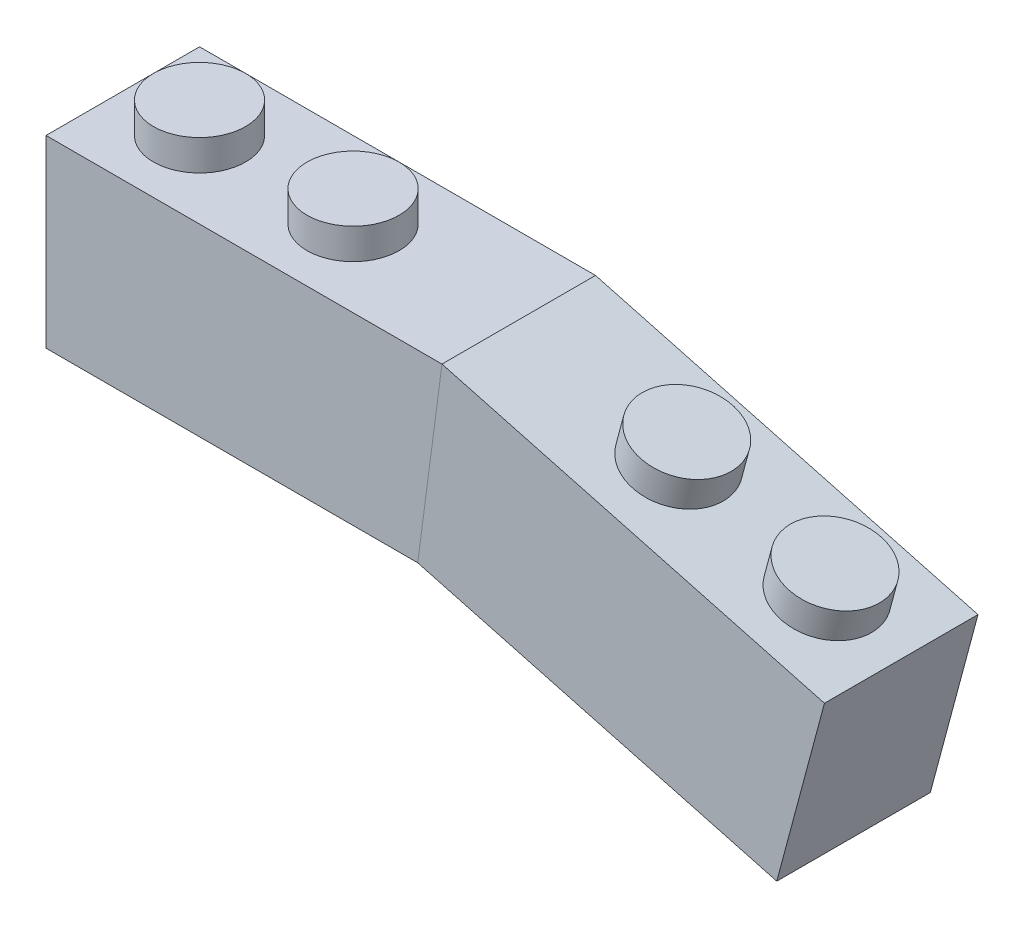
SolidWorks part; units mm, degrees
ref_plane "Front Plane" through (0, 0, 0) normal (0, 0, 1) x (1, 0, 0)
ref_plane "Top Plane" through (0, 0, 0) normal (0, 1, 0) x (1, 0, 0)
ref_plane "Right Plane" through (0, 0, 0) normal (1, 0, 0) x (0, 0, -1)
sketch "Sketch2" plane through (0, 0, 0) normal (1, 0, 0) x (0, 0, -1)
  line L1 (-4, -4.8) -> (4, -4.8)
  line L2 (-4, -4.8) -> (-4, 4.8)
  line L3 (-4, 4.8) -> (4, 4.8)
  line L4 (4, -4.8) -> (4, 4.8)
  line L5 (-4, -4.8) -> (4, 4.8) construction
  line L6 (-4, 4.8) -> (4, -4.8) construction
  point P0 (0, 0)
  dimension "D1" = 9.6
  dimension "D2" = 8
sketch "Sketch3" plane through (0, 0, 0) normal (0, 0, 1) x (1, 0, 0)
  line L0 (0, 0) -> (20, 0)
  line L1 (20, 0) -> (39.3185, -5.1764)
  dimension "D1" = 20
  dimension "D2" = 20
  dimension "D3" = 165
sweep "Sweep1" add profiles "Sketch2" path "Sketch3"
sketch "Sketch4" plane through (0, 4.8, 0) normal (0, 1, 0) x (1, 0, 0)
  line L0 (0, 0) -> (4, 0) construction
  circle A0 centre (4, 0) radius 2.4
  dimension "D2" = 4.8
  dimension "D1" = 4
extrude "Boss-Extrude1" add sketch "Sketch4" along normal blind 1.6
pattern_linear "LPattern1" count 2 spacing 8 along (1, 0, 0) of "Boss-Extrude1"
sketch "Sketch5" plane through (2.5821, 9.6364, 0) normal (0.2588, 0.9659, 0) x (0.9659, -0.2588, 0)
  line L0 (39.3185, 0) -> (35.3185, 0) construction
  line L1 (39.3185, 4) -> (39.3185, -4) construction
  circle A0 centre (35.3185, 0) radius 2.4
  dimension "D2" = 4.8
  dimension "D1" = 4
extrude "Boss-Extrude2" add sketch "Sketch5" along normal blind 1.6
pattern_linear "LPattern2" count 2 spacing 8 along (-0.9659, 0.2588, 0) of "Boss-Extrude2"
shell "Shell1" thickness 1.6
